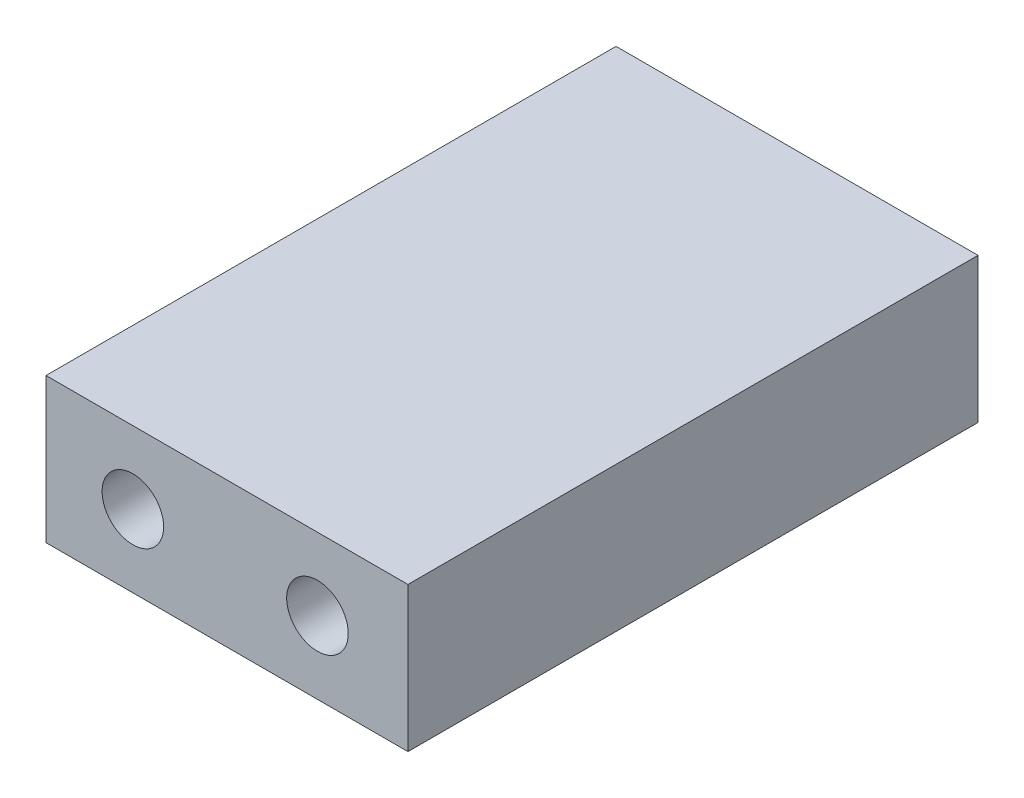
SolidWorks part; units mm, degrees
ref_plane "Plan de face" through (0, 0, 0) normal (0, 0, 1) x (1, 0, 0)
ref_plane "Plan de dessus" through (0, 0, 0) normal (0, 1, 0) x (1, 0, 0)
ref_plane "Plan de droite" through (0, 0, 0) normal (1, 0, 0) x (0, 0, -1)
sketch "Esquisse1" plane through (0, 0, 0) normal (0, 0, 1) x (1, 0, 0)
  line L1 (-17.3148, -5.1717) -> (2.6852, -5.1717)
  line L2 (-17.3148, -5.1717) -> (-17.3148, 2.8283)
  line L3 (-17.3148, 2.8283) -> (2.6852, 2.8283)
  line L4 (2.6852, -5.1717) -> (2.6852, 2.8283)
  dimension "D1" = 8
  dimension "D2" = 20
extrude "Boss.-Extru.1" add sketch "Esquisse1" along normal blind 31.5
hole_wizard "Dégagement M31" positions "Esquisse2" profile "Esquisse4" hole size "M3" standard "ISO" end condition through all
sketch "Esquisse2" plane through (0, 0, 31.5) normal (0, 0, 1) x (1, 0, 0)
  line L0 (2.6852, -5.1717) -> (2.6852, 2.8283) construction
  line L5 (2.6852, 2.8283) -> (-17.3148, 2.8283) construction
  point P0 (-2.3148, -1.1717)
  dimension "D1" = 5
  dimension "D2" = 4
sketch "Esquisse4" plane through (-2.3148, -1.1717, 31.5) normal (1, 0, 0) x (0, -1, 0)
  line L0 (0, 0) -> (0, 31.5)
  line L1 (0, 31.5) -> (1.7, 31.5)
  line L2 (1.7, 31.5) -> (1.7, 0)
  line L5 (1.7, 0) -> (0, 0)
  line L11 (0, -6.35) -> (0, 107.95) construction
  dimension "Diamètre du perçage jusqu'au prochain" = 3.4
  dimension "Profondeur du perçage jusqu'au prochain" = 31.5
pattern_linear "Répétition linéaire1" count 2 spacing 10.2 along (-1, 0, 0) of "Dégagement M31"
